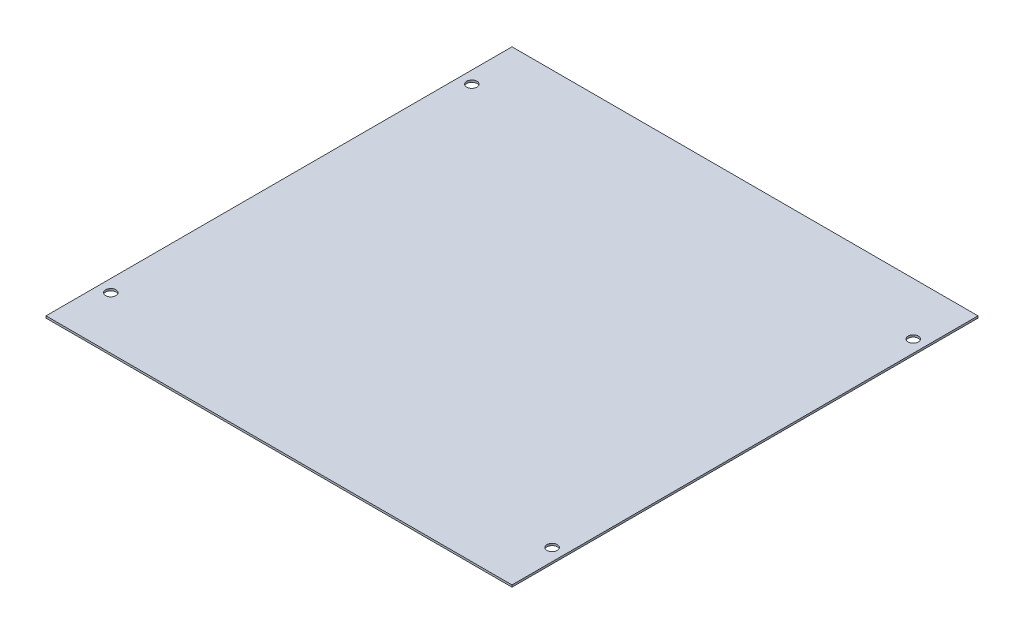
SolidWorks part; units mm, degrees
material "Plain Carbon Steel"
ref_plane "Ground_Plane" through (0, 0, 0) normal (0, 0, 1) x (1, 0, 0)
ref_plane "VehicleCentre_Plane" through (0, 0, 0) normal (0, 1, 0) x (1, 0, 0)
ref_plane "FrontAxle_Plane" through (0, 0, 0) normal (1, 0, 0) x (0, 0, -1)
sketch "Sketch1" plane through (0, 0, 0) normal (0, 1, 0) x (1, 0, 0)
  line L1 (147.5, -147.5) -> (-147.5, -147.5)
  line L2 (147.5, -147.5) -> (147.5, 147.5)
  line L3 (147.5, 147.5) -> (-147.5, 147.5)
  line L4 (-147.5, -147.5) -> (-147.5, 147.5)
  line L5 (147.5, -147.5) -> (-147.5, 147.5) construction
  line L6 (147.5, 147.5) -> (-147.5, -147.5) construction
  point P0 (0, 0)
  dimension "D1" = 295
extrude "Boss-Extrude1" add sketch "Sketch1" along normal blind 1.27
sketch "Sketch2" plane through (0, 1.27, 0) normal (0, 1, 0) x (1, 0, 0)
  line L0 (139.7, 114.3) -> (-139.7, -114.3) construction
  circle A0 centre (-139.7, 114.3) radius 3.25
  circle A1 centre (139.7, 114.3) radius 3.25
  circle A2 centre (139.7, -114.3) radius 3.25
  circle A3 centre (-139.7, -114.3) radius 3.25
  dimension "D1" = 6.5
  dimension "D2" = 279.4
  dimension "D3" = 228.6
extrude "Cut-Extrude1" cut sketch "Sketch2" against normal through all
